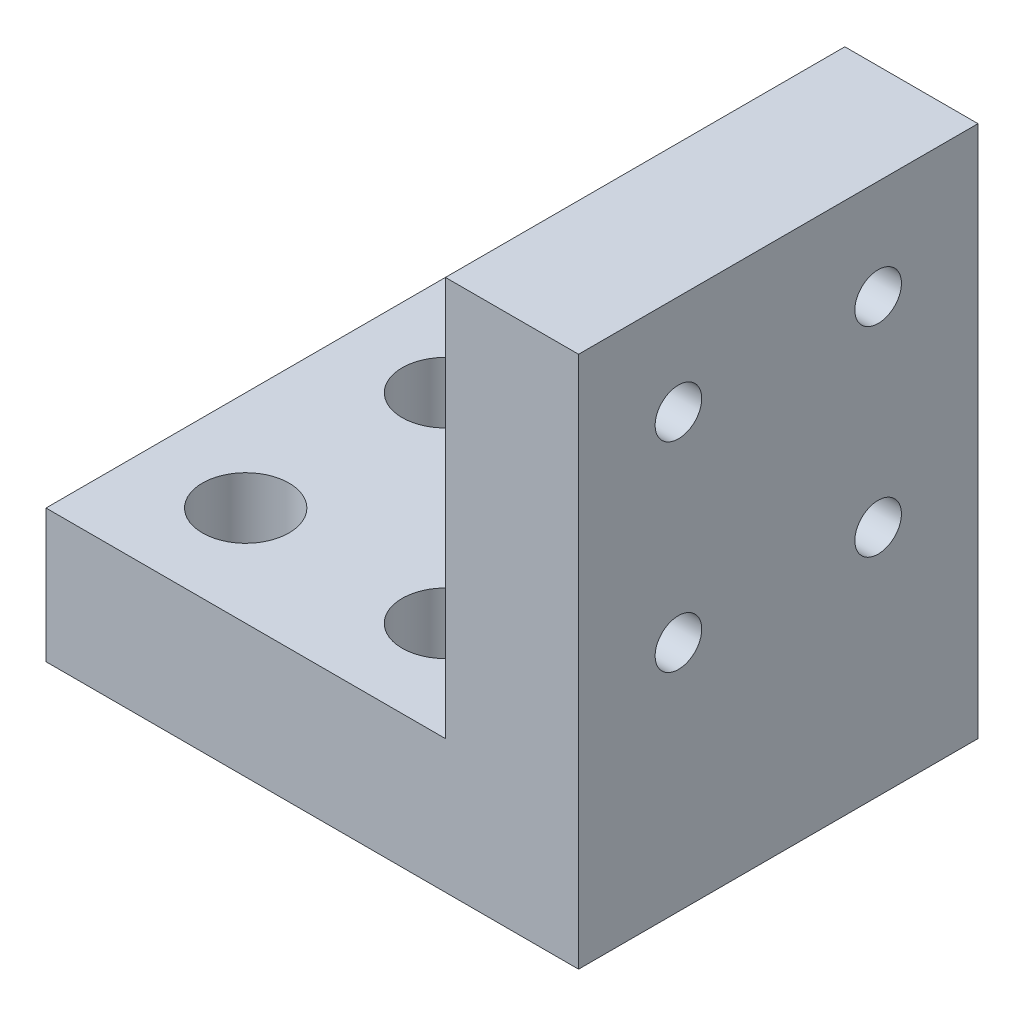
SolidWorks part; units mm, degrees
ref_plane "Plano frontal" through (0, 0, 0) normal (0, 0, 1) x (1, 0, 0)
ref_plane "Plano superior" through (0, 0, 0) normal (0, 1, 0) x (1, 0, 0)
ref_plane "Plano direito" through (0, 0, 0) normal (1, 0, 0) x (0, 0, -1)
sketch "Esboço1" plane through (0, 0, 0) normal (0, 1, 0) x (1, 0, 0)
  line L1 (0, 0) -> (40, 0)
  line L2 (0, 0) -> (0, 30)
  line L3 (0, 30) -> (40, 30)
  line L4 (40, 0) -> (40, 30)
  dimension "D1" = 30
  dimension "D2" = 40
extrude "Ressalto-extrusão1" add sketch "Esboço1" along normal blind 10
sketch "Esboço2" plane through (0, 10, 0) normal (0, 1, 0) x (1, 0, 0)
  line L0 (0, 0) -> (40, 0) construction
  line L1 (40, 30) -> (30, 30)
  line L2 (40, 30) -> (40, 0)
  line L3 (40, 0) -> (30, 0)
  line L4 (30, 30) -> (30, 0)
  dimension "D1" = 10
extrude "Ressalto-extrusão2" add sketch "Esboço2" along normal blind 30
sketch "Esboço4" plane through (0, 10, 0) normal (0, 1, 0) x (1, 0, 0)
  line L0 (0, 30) -> (0, 0) construction
  line L1 (0, 15) -> (30, 15) construction
  line L2 (30, 30) -> (30, 0) construction
  line L3 (30, 30) -> (0, 30) construction
  circle A0 centre (7.5, 22.5) radius 3.25
  circle A1 centre (22.5, 22.5) radius 3.25
  circle A2 centre (22.5, 7.5) radius 3.25
  circle A3 centre (7.5, 7.5) radius 3.25
  dimension "D5" = 6.5
  dimension "D1" = 7.5
  dimension "D2" = 7.5
  dimension "D3" = 2
  dimension "D4" = 2
extrude "Corte-extrusão1" cut sketch "Esboço4" against normal blind 6
sketch "Esboço5" plane through (0, 10, 0) normal (0, 1, 0) x (1, 0, 0)
  circle A0 centre (7.5, 22.5) radius 1.75
  circle A1 centre (22.5, 22.5) radius 1.75
  circle A2 centre (22.5, 7.5) radius 1.75
  circle A3 centre (7.5, 7.5) radius 1.75
  dimension "D1" = 3.5
  dimension "D2" = 2
  dimension "D3" = 2
extrude "Corte-extrusão2" cut sketch "Esboço5" against normal up to surface (10 mm away) up to face at (20, 0, -15)
sketch "Esboço6" plane through (30, 0, 0) normal (-1, 0, 0) x (0, 0, 1)
  line L0 (-15, 40) -> (-15, 10) construction
  line L1 (-30, 40) -> (0, 40) construction
  line L2 (-30, 10) -> (0, 10) construction
  line L3 (0, 40) -> (0, 10) construction
  circle A0 centre (-7.5, 32.5) radius 3.25
  circle A1 centre (-22.5, 32.5) radius 3.25
  circle A2 centre (-22.5, 17.5) radius 3.25
  circle A3 centre (-7.5, 17.5) radius 3.25
  dimension "D1" = 6.5
  dimension "D2" = 7.5
  dimension "D3" = 7.5
  dimension "D4" = 2
  dimension "D5" = 2
extrude "Corte-extrusão3" cut sketch "Esboço6" against normal blind 6
sketch "Esboço7" plane through (30, 0, 0) normal (-1, 0, 0) x (0, 0, 1)
  circle A0 centre (-22.5, 32.5) radius 1.75
  circle A1 centre (-7.5, 32.5) radius 1.75
  circle A2 centre (-7.5, 17.5) radius 1.75
  circle A3 centre (-22.5, 17.5) radius 1.75
  dimension "D1" = 3.5
  dimension "D2" = 2
  dimension "D3" = 2
extrude "Corte-extrusão4" cut sketch "Esboço7" against normal up to surface (10 mm away) up to face at (40, 20, -15)
